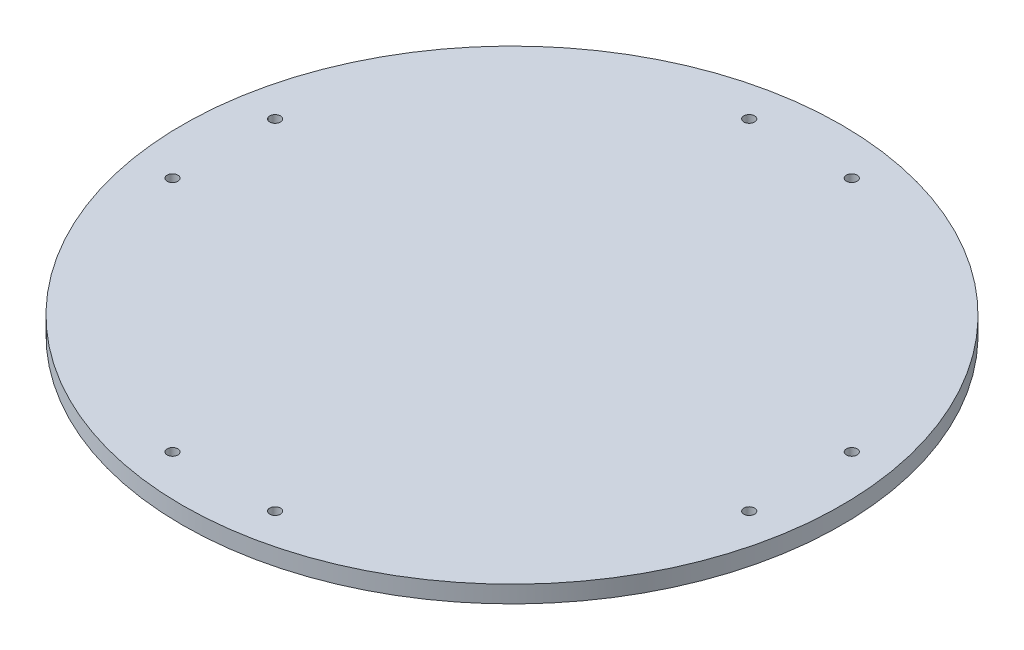
SolidWorks part; units mm, degrees
ref_plane "Front Plane" through (0, 0, 0) normal (0, 0, 1) x (1, 0, 0)
ref_plane "Top Plane" through (0, 0, 0) normal (0, 1, 0) x (1, 0, 0)
ref_plane "Right Plane" through (0, 0, 0) normal (1, 0, 0) x (0, 0, -1)
sketch "Sketch1" plane through (0, 0, 0) normal (0, 1, 0) x (1, 0, 0)
  circle A0 centre (0, 0) radius 122.4
  dimension "D1" = 244.8
extrude "Boss-Extrude1" add sketch "Sketch1" along normal blind 6.35
sketch "Sketch2" plane through (0, 6.35, 0) normal (0, 1, 0) x (1, 0, 0)
  line L0 (0, 122.4) -> (0, -122.4) construction
  line L1 (-122.4, 0) -> (122.4, 0) construction
  line L2 (-25.4, -119.7355) -> (25.4, -119.7355) construction
  circle A0 centre (0, 0) radius 122.4 construction
  circle A1 centre (-19.05, -107.0355) radius 1.9939
  circle A2 centre (19.05, -107.0355) radius 1.9939
  dimension "D2" = 3.9878
  dimension "D1" = 50.8
  dimension "D3" = 6.35
  dimension "D4" = 6.35
  dimension "D5" = 12.7
extrude "Cut-Extrude1" cut sketch "Sketch2" against normal through all
pattern_circular "CirPattern1" count 4 every 90 about axis through (0, 0, -0.0568) along (0, 1, 0) of "Cut-Extrude1"
sketch "Sketch4" plane through (0, 6.35, 0) normal (0, 1, 0) x (1, 0, 0)
  circle A0 centre (0, 0) radius 40
  dimension "D1" = 80
